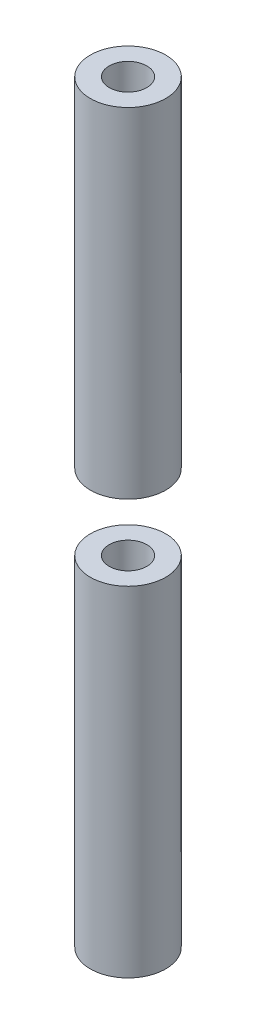
SolidWorks part; units mm, degrees
ref_plane "Front Plane" through (0, 0, 0) normal (0, 0, 1) x (1, 0, 0)
ref_plane "Top Plane" through (0, 0, 0) normal (0, 1, 0) x (1, 0, 0)
ref_plane "Right Plane" through (0, 0, 0) normal (1, 0, 0) x (0, 0, -1)
sketch "Sketch2" plane through (0, 0, 0) normal (0, 1, 0) x (1, 0, 0)
  circle A0 centre (0, 0) radius 2.5
  dimension "D1" = 5
extrude "Boss-Extrude1" add sketch "Sketch2" along normal blind 60
sketch "Sketch4" plane through (0, 0, 0) normal (1, 0, 0) x (0, 0, -1)
  line L0 (0, 32.5) -> (14.1384, 32.5)
  line L1 (14.1384, 32.5) -> (14.1384, 27.5)
  line L2 (14.1384, 27.5) -> (-5.1924, 27.5)
  line L3 (2.5, 60) -> (-2.5, 60) construction
  line L5 (0, 32.5) -> (-5.1924, 32.5)
  line L6 (-5.1924, 32.5) -> (-5.1924, 27.5)
  dimension "D1" = 27.5
  dimension "D2" = 5
extrude "Cut-Extrude1" cut sketch "Sketch4" against normal mid plane 10
sketch "Sketch6" plane through (0, 0, 0) normal (0, 1, 0) x (1, 0, 0)
  circle A0 centre (0, 0) radius 1.25
  dimension "D1" = 2.5
extrude "Cut-Extrude2" cut sketch "Sketch6" along normal blind 60
sketch "Sketch7" plane through (0, 0, 0) normal (1, 0, 0) x (0, 0, -1)
  line L1 (-2.5, 60) -> (2.526, 60)
  line L2 (-2.5, 60) -> (-2.5, 55)
  line L3 (-2.5, 55) -> (2.526, 55)
  line L4 (2.526, 60) -> (2.526, 55)
  dimension "D1" = 5
extrude "Cut-Extrude3" cut sketch "Sketch7" against normal mid plane 50
sketch "Sketch8" plane through (0, 0, 0) normal (1, 0, 0) x (0, 0, -1)
  line L0 (-2.5, 0) -> (2.5, 0) construction
  line L1 (-2.5, 0) -> (2.5, 0)
  line L2 (-2.5, 0) -> (-2.5, 5)
  line L3 (-2.5, 5) -> (2.5, 5)
  line L4 (2.5, 0) -> (2.5, 5)
  line L5 (2.5, 0) -> (2.5, 27.5) construction
  dimension "D1" = 5
extrude "Cut-Extrude4" cut sketch "Sketch8" against normal mid plane 50
